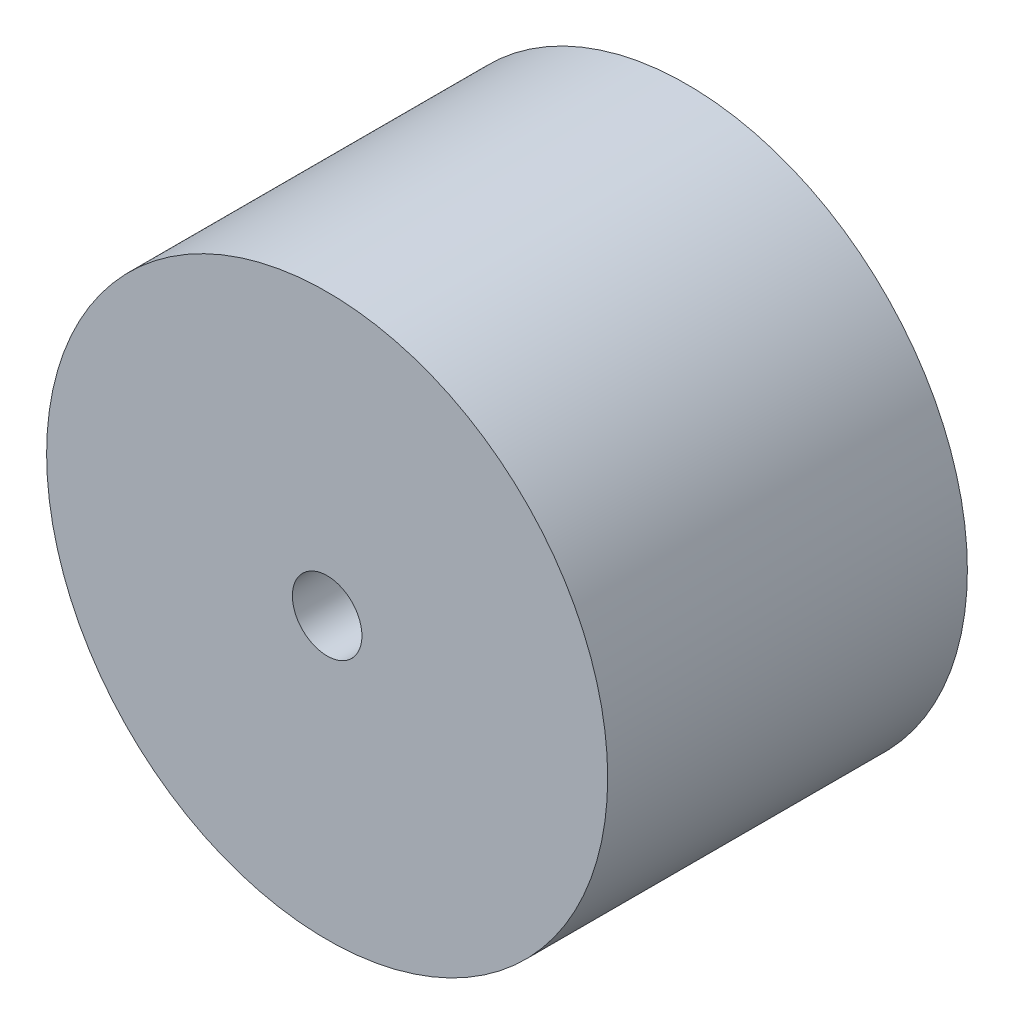
SolidWorks part; units mm, degrees
ref_plane "Front Plane" through (0, 0, 0) normal (0, 0, 1) x (1, 0, 0)
ref_plane "Top Plane" through (0, 0, 0) normal (0, 1, 0) x (1, 0, 0)
ref_plane "Right Plane" through (0, 0, 0) normal (1, 0, 0) x (0, 0, -1)
sketch "Sketch1" plane through (0, 0, 0) normal (0, 0, 1) x (1, 0, 0)
  circle A0 centre (0, 0) radius 409.702
  circle A1 centre (0, 0) radius 50.8
  dimension "D1" = 819.404
  dimension "D2" = 101.6
extrude "Boss-Extrude1" add sketch "Sketch1" along normal blind 525.272
